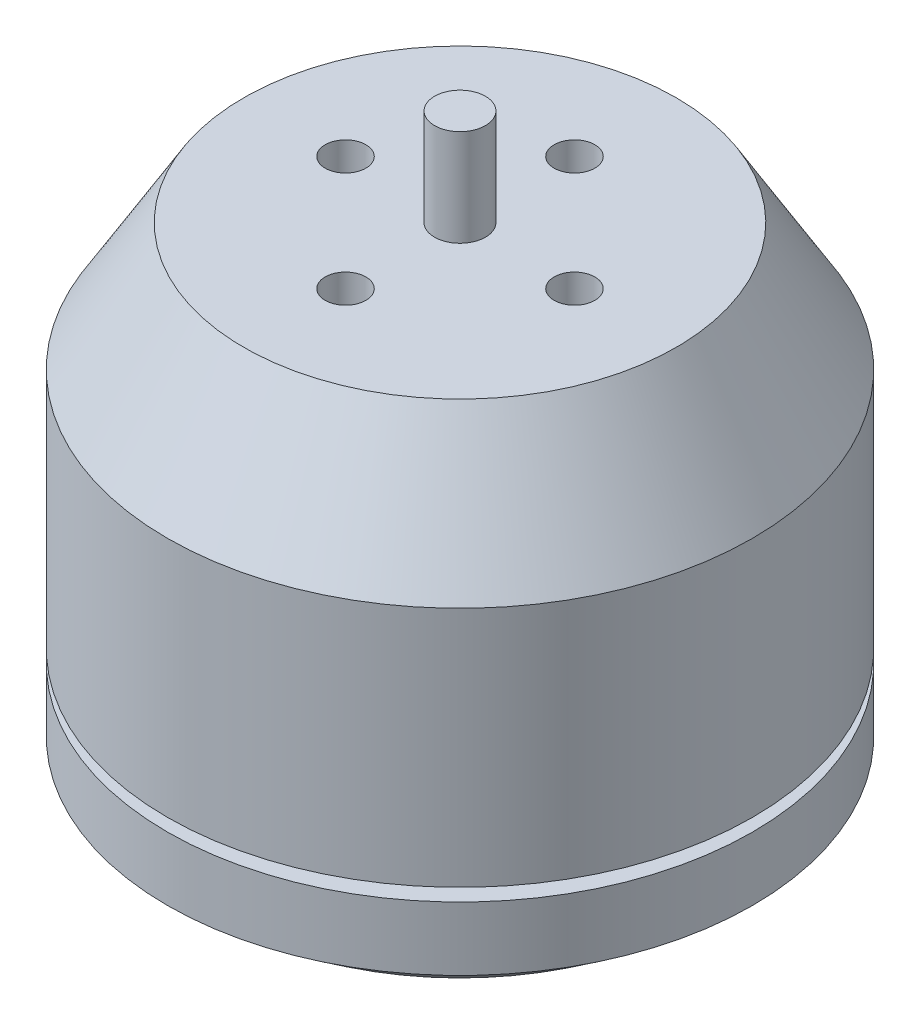
SolidWorks part; units mm, degrees
ref_plane "Ebene vorne" through (0, 0, 0) normal (0, 0, 1) x (1, 0, 0)
ref_plane "Ebene oben" through (0, 0, 0) normal (0, 1, 0) x (1, 0, 0)
ref_plane "Ebene rechts" through (0, 0, 0) normal (1, 0, 0) x (0, 0, -1)
sketch "Skizze1" plane through (0, 0, 0) normal (0, 0, 1) x (1, 0, 0)
  line L0 (0, 0) -> (0, 23.8) construction
  line L1 (9.5, 1) -> (3, 1)
  line L2 (9.5, 1) -> (11.5, 2.5)
  line L3 (11.5, 2.5) -> (11.5, 5)
  line L4 (11.5, 5) -> (10.5, 5)
  line L5 (10.5, 5) -> (10.5, 5.5)
  line L6 (10.5, 5.5) -> (11.5, 5.5)
  line L7 (11.5, 5.5) -> (11.5, 15)
  line L8 (11.5, 15) -> (8.5, 20)
  line L9 (8.5, 20) -> (1, 20)
  line L10 (1, 20) -> (1, 23.8)
  line L11 (1, 23.8) -> (0, 23.8)
  line L12 (3, 1) -> (3, 1.3)
  line L13 (3, 1.3) -> (1, 1.3)
  line L14 (1, 1.3) -> (1, 0)
  line L15 (1, 0) -> (0, 0)
  line L16 (0, 0) -> (0, 23.8)
  dimension "D1" = 2
  dimension "D2" = 1
  dimension "D3" = 19
  dimension "D4" = 23
  dimension "D5" = 19
  dimension "D6" = 2.5
  dimension "D7" = 0.5
  dimension "D8" = 5
  dimension "D9" = 17
  dimension "D10" = 21
  dimension "D11" = 6
  dimension "D12" = 0.3
  dimension "D13" = 23.8
revolve "Rotation1" add sketch "Skizze1" angle 360 about L0
hole_wizard "M2 Gewindebohrung1" positions "Skizze5" profile "Skizze4" tap size "M2" standard "DIN"
sketch "Skizze5" plane through (0, 20, 0) normal (0, 1, 0) x (1, 0, 0)
  line L0 (0, 4.5) -> (0, 0) construction
  line L1 (0, 0) -> (0, -4.5) construction
  line L3 (4.5, 0) -> (0, 0) construction
  line L4 (0, 0) -> (-4.5, 0) construction
  point P0 (-4.5, 0)
  point P6 (0, 4.5)
  point P7 (4.5, 0)
  point P8 (0, -4.5)
  dimension "D2" = 9
  dimension "D1" = 4
sketch "Skizze4" plane through (-4.5, 20, 0) normal (1, 0, 0) x (0, 0, 1)
  line L0 (0, 0) -> (0, 3.4807)
  line L1 (0, 3.4807) -> (0.8, 3)
  line L2 (0.8, 3) -> (0.8, 0)
  line L5 (0.8, 0) -> (0, 0)
  line L10 (0, 3.4807) -> (-0.8, 3) construction
  line L11 (0, -6.35) -> (0, 107.95) construction
  dimension "Bohrerdurchmesser" = 1.6
  dimension "Bohrungstiefe" = 3
  dimension "Spitzenwinkel" = 118
cosmetic thread "Bohrungsgewinde1" parameters "D1"=3, "D2"=2
cosmetic thread "Bohrungsgewinde2" parameters "D1"=3, "D2"=2
cosmetic thread "Bohrungsgewinde3" parameters "D1"=3, "D2"=2
cosmetic thread "Bohrungsgewinde4" parameters "D1"=3, "D2"=2
hole_wizard "M2 Gewindebohrung2" positions "Skizze7" profile "Skizze6" tap size "M2" standard "DIN"
sketch "Skizze7" plane through (0, 1, 0) normal (0, -1, 0) x (-1, 0, 0)
  line L0 (-6, 0) -> (0, 0) construction
  line L1 (0, 0) -> (6, 0) construction
  line L3 (0, 8) -> (0, 0) construction
  line L4 (0, 0) -> (0, -8) construction
  point P0 (0, 8)
  point P2 (0, -8)
  point P4 (6, 0)
  point P6 (-6, 0)
  dimension "D1" = 16
  dimension "D2" = 12
sketch "Skizze6" plane through (0, 1, -8) normal (1, 0, 0) x (0, 0, -1)
  line L0 (0, 0) -> (0, 5.4807)
  line L1 (0, 5.4807) -> (0.8, 5)
  line L2 (0.8, 5) -> (0.8, 0)
  line L5 (0.8, 0) -> (0, 0)
  line L10 (0, 5.4807) -> (-0.8, 5) construction
  line L11 (0, -6.35) -> (0, 107.95) construction
  dimension "Bohrerdurchmesser" = 1.6
  dimension "Bohrungstiefe" = 5
  dimension "Spitzenwinkel" = 118
cosmetic thread "Bohrungsgewinde5" parameters "D1"=3, "D2"=2
cosmetic thread "Bohrungsgewinde6" parameters "D1"=3, "D2"=2
cosmetic thread "Bohrungsgewinde7" parameters "D1"=3, "D2"=2
cosmetic thread "Bohrungsgewinde8" parameters "D1"=3, "D2"=2
